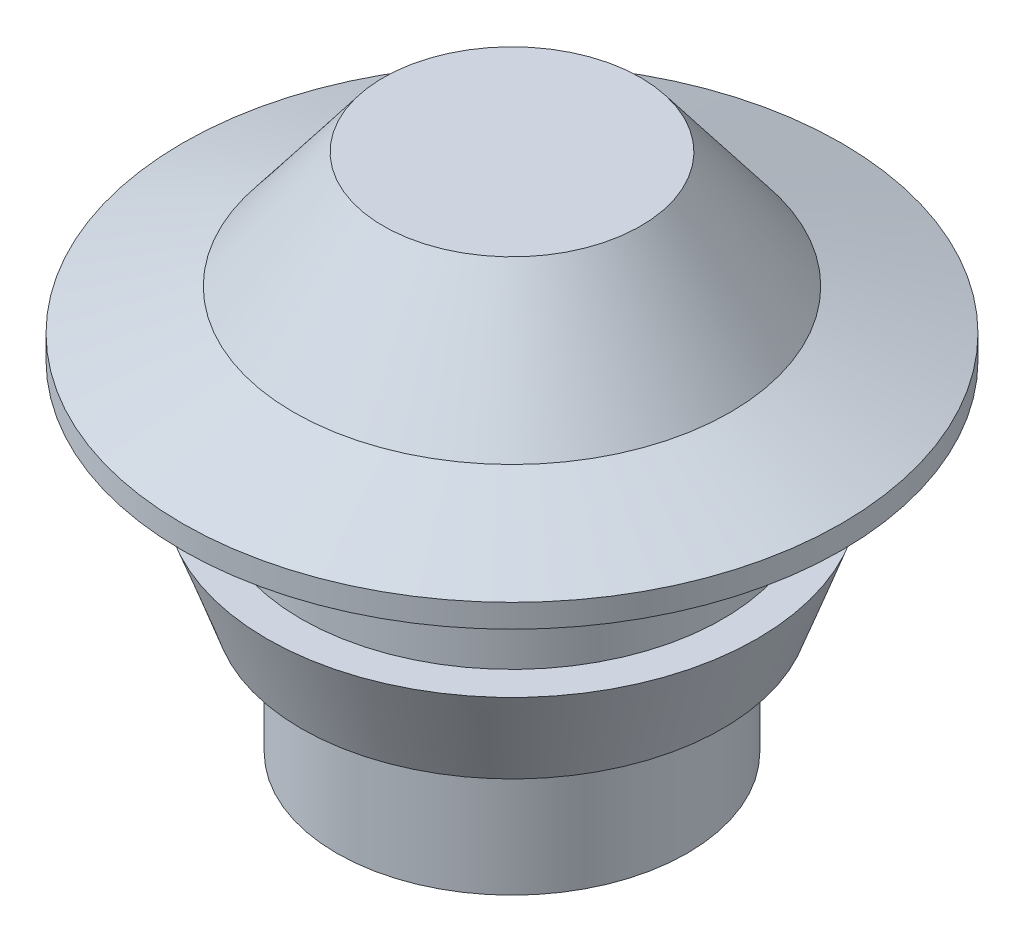
SolidWorks part; units mm, degrees
ref_plane "Спереди" through (0, 0, 0) normal (0, 0, 1) x (1, 0, 0)
ref_plane "Сверху" through (0, 0, 0) normal (0, 1, 0) x (1, 0, 0)
ref_plane "Справа" through (0, 0, 0) normal (1, 0, 0) x (0, 0, -1)
other "Configuration Table"
sketch "Эскиз1" plane through (0, 0, 0) normal (0, 0, 1) x (1, 0, 0)
  line L0 (0, 0) -> (0, 22.325) construction
  line L1 (0, 0) -> (-7.525, 0)
  line L2 (-7.525, 0) -> (-7.525, 5.4)
  line L3 (-7.525, 5.4) -> (-9.05, 5.4)
  line L4 (-9.05, 5.4) -> (-9.05, 9.475) construction
  line L5 (-9.05, 9.475) -> (-10.525, 9.475)
  line L6 (-9.05, 5.4) -> (-10.525, 9.475)
  line L7 (-9.05, 9.475) -> (-9.05, 14.575)
  line L8 (-9.05, 14.575) -> (-14.15, 14.575)
  line L9 (-14.15, 14.575) -> (-14.15, 15.575)
  line L11 (-14.15, 15.575) -> (-9.375, 17.325)
  line L13 (0, 22.325) -> (-5.525, 22.325)
  line L14 (-5.525, 22.325) -> (-9.375, 17.325)
  line L15 (0, 0) -> (0, 22.325)
  point P3 (0, 0)
  dimension "D1" = 22.325
  dimension "D2" = 15.05
  dimension "D3" = 5.4
  dimension "D4" = 18.1
  dimension "D5" = 4.075
  dimension "D6" = 21.05
  dimension "D7" = 5.1
  dimension "D8" = 28.3
  dimension "D9" = 1
  dimension "D10" = 5
  dimension "D11" = 18.75
  dimension "D12" = 11.05
revolve "Повернуть1" add sketch "Эскиз1" angle 360 about L15
sketch "Эскиз2" plane through (0, 0, 0) normal (0, -1, 0) x (1, 0, 0)
  circle A0 centre (0, 0) radius 5.6
  dimension "D1" = 11.2
extrude "Вырез-Вытянуть1" cut sketch "Эскиз2" against normal blind 9.075 and the other way through all
